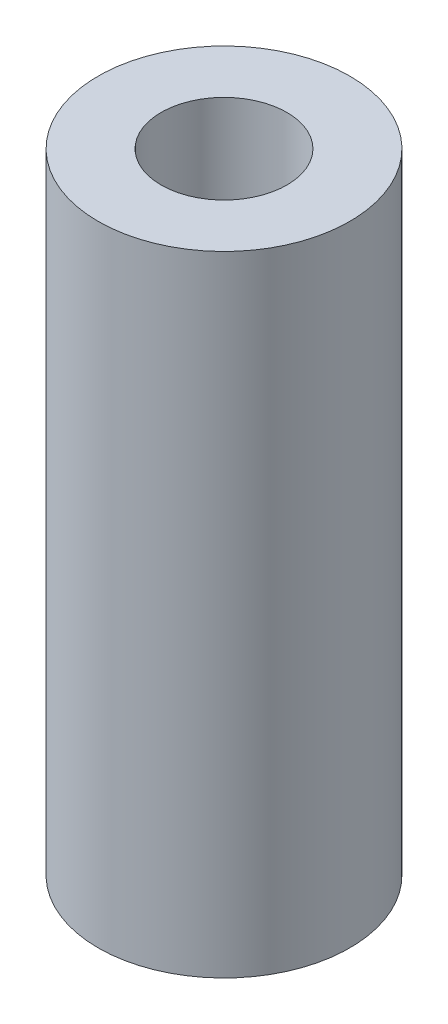
SolidWorks part; units mm, degrees
ref_plane "Front Plane" through (0, 0, 0) normal (0, 0, 1) x (1, 0, 0)
ref_plane "Top Plane" through (0, 0, 0) normal (0, 1, 0) x (1, 0, 0)
ref_plane "Right Plane" through (0, 0, 0) normal (1, 0, 0) x (0, 0, -1)
sketch "Sketch1" plane through (0, 0, 0) normal (0, 1, 0) x (1, 0, 0)
  circle A0 centre (0, 0) radius 6.35
  circle A1 centre (0, 0) radius 3.175
extrude "Boss-Extrude1" add sketch "Sketch1" along normal blind 31.75
